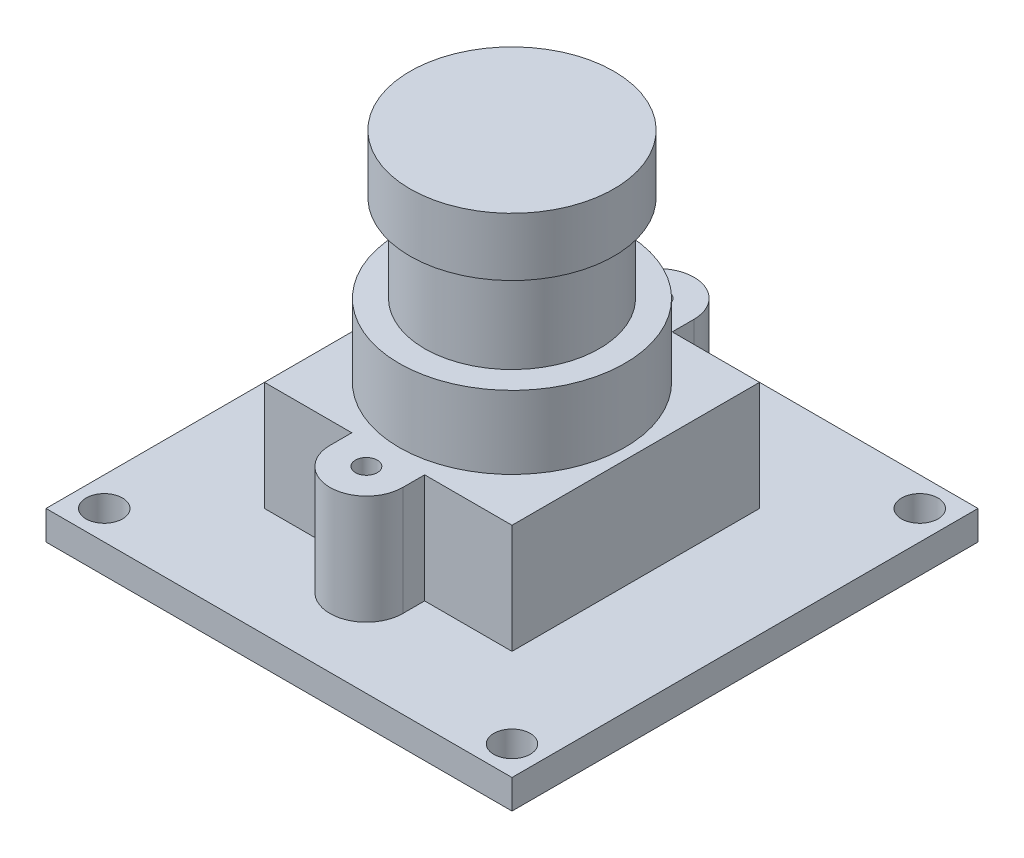
SolidWorks part; units mm, degrees
ref_plane "前视基准面" through (0, 0, 0) normal (0, 0, 1) x (1, 0, 0)
ref_plane "上视基准面" through (0, 0, 0) normal (0, 1, 0) x (1, 0, 0)
ref_plane "右视基准面" through (0, 0, 0) normal (1, 0, 0) x (0, 0, -1)
sketch "草图1" plane through (0, 0, 0) normal (0, 1, 0) x (1, 0, 0)
  line L1 (-16, -16) -> (16, -16)
  line L2 (-16, -16) -> (-16, 16)
  line L3 (-16, 16) -> (16, 16)
  line L4 (16, -16) -> (16, 16)
  line L5 (-16, -16) -> (16, 16) construction
  line L6 (-16, 16) -> (16, -16) construction
  line L7 (-14, -14) -> (14, -14) construction
  line L8 (-14, -14) -> (-14, 14) construction
  line L9 (-14, 14) -> (14, 14) construction
  line L10 (14, -14) -> (14, 14) construction
  line L11 (-14, -14) -> (14, 14) construction
  line L12 (-14, 14) -> (14, -14) construction
  circle A0 centre (-14, 14) radius 1.25
  circle A1 centre (14, 14) radius 1.25
  circle A2 centre (14, -14) radius 1.25
  circle A3 centre (-14, -14) radius 1.25
  point P0 (0, 0)
  point P6 (0, 0)
  dimension "D4" = 2.5
  dimension "D5" = 2.5
  dimension "D6" = 2.5
  dimension "D7" = 2.5
  dimension "D1" = 32
  dimension "D2" = 32
  dimension "D3" = 28
extrude "凸台-拉伸1" add sketch "草图1" along normal blind 2
sketch "草图2" plane through (0, 2, 0) normal (0, 1, 0) x (1, 0, 0)
  line L0 (-2.5, -10) -> (-2.5, -8.5)
  line L1 (-8.5, -8.5) -> (-2.5, -8.5)
  line L2 (-8.5, -8.5) -> (-8.5, 8.5)
  line L3 (-8.5, 8.5) -> (-2.5, 8.5)
  line L4 (8.5, -8.5) -> (8.5, 8.5)
  line L5 (-8.5, -8.5) -> (8.5, 8.5) construction
  line L6 (-8.5, 8.5) -> (8.5, -8.5) construction
  line L7 (2.5, -10) -> (2.5, -8.5)
  line L8 (-2.5, 10) -> (-2.5, 8.5)
  line L9 (2.5, 10) -> (2.5, 8.5)
  line L10 (2.5, -8.5) -> (8.5, -8.5)
  line L11 (2.5, 8.5) -> (8.5, 8.5)
  circle A0 centre (0, 10) radius 0.75
  circle A1 centre (0, -10) radius 0.75
  arc A2 (-2.5, -10) -> (2.5, -10) centre (0, -10) ccw
  arc A3 (2.5, 10) -> (-2.5, 10) centre (0, 10) ccw
  point P0 (0, 0)
  dimension "D3" = 5
  dimension "D4" = 5
  dimension "D5" = 1.5
  dimension "D6" = 1.5
  dimension "D1" = 17
  dimension "D2" = 17
  dimension "D7" = 1.5
  dimension "D8" = 1.5
extrude "凸台-拉伸2" add sketch "草图2" along normal blind 7.5
sketch "草图3" plane through (0, 9.5, 0) normal (0, 1, 0) x (1, 0, 0)
  circle A0 centre (0, 0) radius 7.75
  dimension "D1" = 15.5
extrude "凸台-拉伸3" add sketch "草图3" along normal blind 5
sketch "草图4" plane through (0, 14.5, 0) normal (0, 1, 0) x (1, 0, 0)
  circle A0 centre (0, 0) radius 6
  dimension "D1" = 12
extrude "凸台-拉伸4" add sketch "草图4" along normal blind 6
sketch "草图5" plane through (0, 20.5, 0) normal (0, 1, 0) x (1, 0, 0)
  circle A0 centre (0, 0) radius 7
  dimension "D1" = 14
extrude "凸台-拉伸5" add sketch "草图5" along normal blind 4
